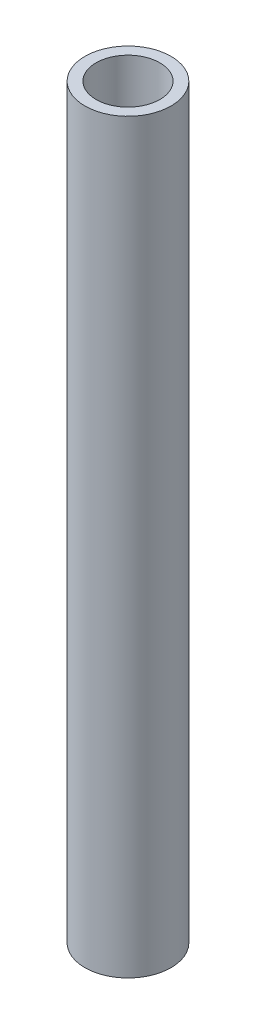
SolidWorks part; units mm, degrees
material "PVC Rigid"
ref_plane "Front Plane" through (0, 0, 0) normal (0, 0, 1) x (1, 0, 0)
ref_plane "Top Plane" through (0, 0, 0) normal (0, 1, 0) x (1, 0, 0)
ref_plane "Right Plane" through (0, 0, 0) normal (1, 0, 0) x (0, 0, -1)
sketch "Sketch1" plane through (0, 0, 0) normal (0, 1, 0) x (1, 0, 0)
  circle A0 centre (0, 0) radius 10.668
  circle A1 centre (0, 0) radius 7.8994
  dimension "D1" = 21.336
  dimension "D2" = 15.7988
  dimension "D3" = 2.7686
extrude "Boss-Extrude1" add sketch "Sketch1" along normal blind 184.9437
